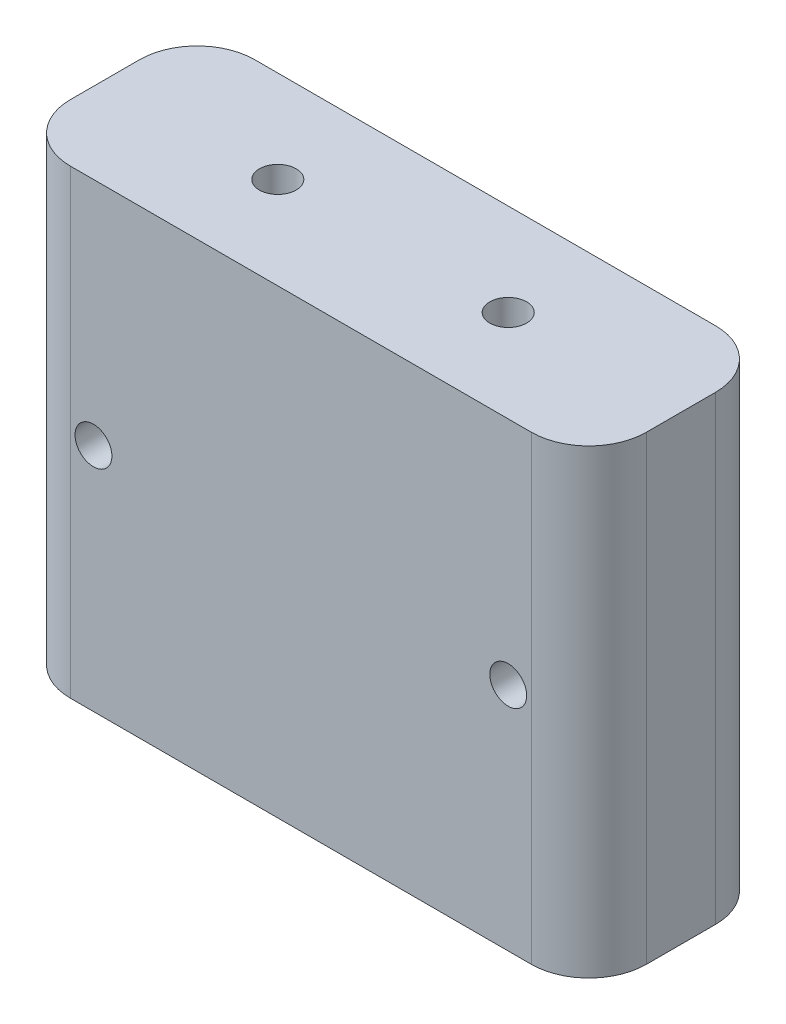
SolidWorks part; units mm, degrees
ref_plane "Front Plane" through (0, 0, 0) normal (0, 0, 1) x (1, 0, 0)
ref_plane "Top Plane" through (0, 0, 0) normal (0, 1, 0) x (1, 0, 0)
ref_plane "Right Plane" through (0, 0, 0) normal (1, 0, 0) x (0, 0, -1)
sketch "Sketch1" plane through (0, 0, 0) normal (0, 1, 0) x (1, 0, 0)
  line L0 (15, 8) -> (35, 8) construction
  line L1 (0, 0) -> (50, 0)
  line L2 (0, 0) -> (0, 16)
  line L3 (0, 16) -> (50, 16)
  line L4 (50, 0) -> (50, 16)
  line L5 (25, 0) -> (25, 16) construction
  circle A0 centre (15, 8) radius 1.6
  circle A1 centre (35, 8) radius 1.6
  point P4 (25, 8)
  point P5 (8.9403, 8.1977)
  point P13 (0, 0)
  point P14 (27.3635, 7.9487)
  point P15 (25, 8)
  dimension "D2" = 3.2
  dimension "D1" = 16
  dimension "D3" = 15
  dimension "D4" = 20
extrude "Boss-Extrude1" add sketch "Sketch1" along normal blind 40
sketch "Sketch2" plane through (0, 0, 0) normal (0, 0, 1) x (1, 0, 0)
  line L0 (7, 20) -> (43, 20) construction
  line L2 (0, 0) -> (50, 0) construction
  line L3 (25, 0) -> (25, 40) construction
  line L4 (0, 40) -> (50, 40) construction
  circle A0 centre (7, 20) radius 1.6
  circle A1 centre (43, 20) radius 1.6
  point P8 (25, 20)
  point P11 (0, 0)
  dimension "D1" = 3.2
  dimension "D2" = 18
extrude "Cut-Extrude1" cut sketch "Sketch2" against normal through all
fillet "Fillet1" radius 5 4 edges at (50, 20, -16) (0, 20, -16) (50, 20, 0) (0, 20, 0)
